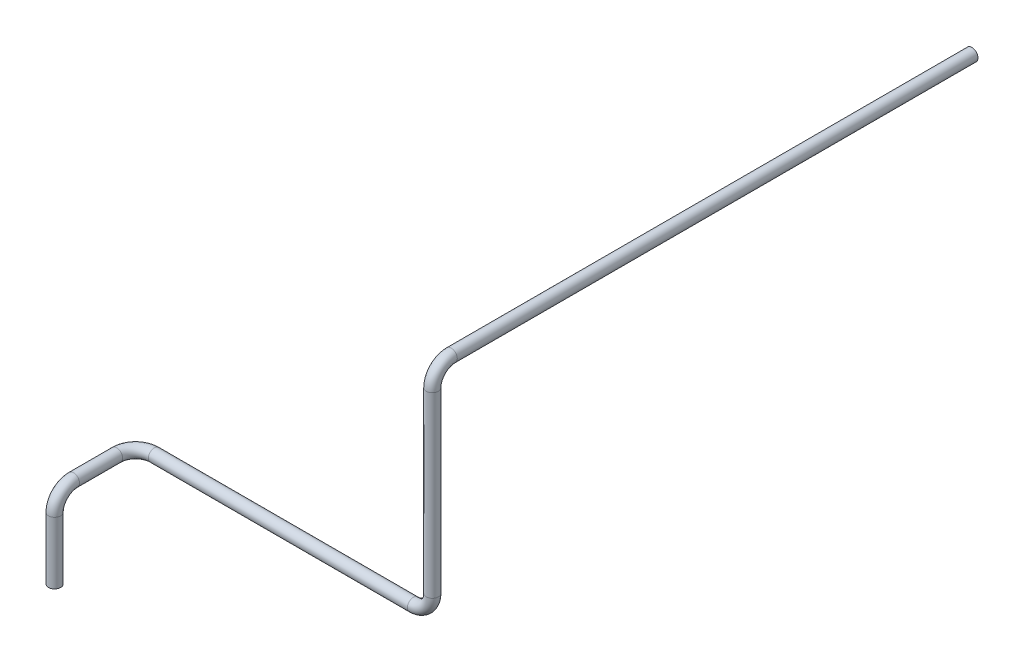
SolidWorks part; units mm, degrees
ref_plane "Alzado" through (0, 0, 0) normal (0, 0, 1) x (1, 0, 0)
ref_plane "Planta" through (0, 0, 0) normal (0, 1, 0) x (1, 0, 0)
ref_plane "Vista lateral" through (0, 0, 0) normal (1, 0, 0) x (0, 0, -1)
sketch "Croquis1" plane through (0, 0, 0) normal (0, 0, 1) x (1, 0, 0)
  circle A0 centre (0, 0) radius 22.5
  dimension "D1" = 45
extrude "Saliente-Extruir1" add sketch "Croquis1" along normal blind 100
sketch3d "Croquis3D1"
  line L0 (0, 0, 100) -> (0, 0, 1930)
  line L1 (0, 0, 100) -> (0, 0, 0) construction
  line L2 (0, -70, 2000) -> (0, -730, 2000)
  line L3 (-70, -800, 2000) -> (-1030, -800, 2000)
  line L4 (-1100, -800, 2070) -> (-1100, -800, 2230)
  line L5 (-1100, -870, 2300) -> (-1100, -1100, 2300)
  arc A0 (-1100, -800, 2230) -> (-1100, -870, 2300) centre (-1100, -870, 2230) ccw
  arc A1 (-1030, -800, 2000) -> (-1100, -800, 2070) centre (-1030, -800, 2070) ccw
  arc A2 (0, -730, 2000) -> (-70, -800, 2000) centre (-70, -730, 2000) ccw
  arc A3 (0, 0, 1930) -> (0, -70, 2000) centre (0, -70, 1930) ccw
  point P10 (-1100, -800, 2300)
  point P11 (-1030, -870, 2230)
  point P14 (-1100, -800, 2000)
  point P15 (-1030, -730, 2070)
  point P18 (0, -800, 2000)
  point P19 (-70, -730, 1930)
  point P22 (0, 0, 2000)
  point P23 (70, -70, 1930)
  dimension "D6" = 70
  dimension "D1" = 1900
  dimension "D2" = 800
  dimension "D3" = 1100
  dimension "D4" = 300
  dimension "D5" = 300
sketch "Croquis3" plane through (0, 0, 100) normal (0, 0, 1) x (1, 0, 0)
  circle A0 centre (0, 0) radius 22.5
sweep "Barrer1" add profiles "Croquis3" path "Croquis3D1"
